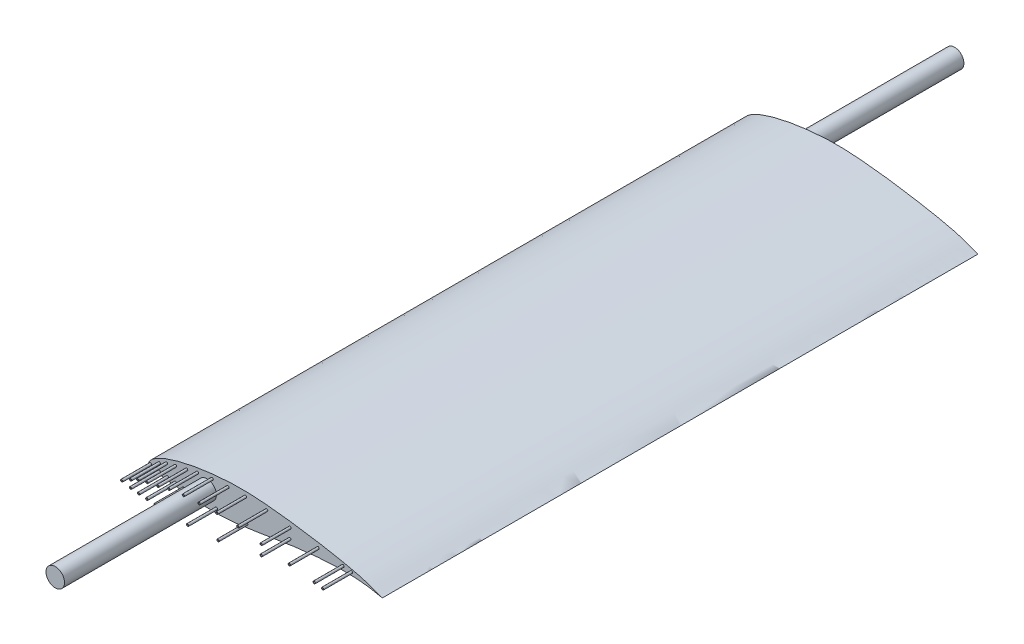
SolidWorks part; units mm, degrees
ref_plane "Front Plane" through (0, 0, 0) normal (0, 0, 1) x (1, 0, 0)
ref_plane "Top Plane" through (0, 0, 0) normal (0, 1, 0) x (1, 0, 0)
ref_plane "Right Plane" through (0, 0, 0) normal (1, 0, 0) x (0, 0, -1)
curve "Curve3"
  spline degree 3 poles (99.2573, 0.1883, 0) (100.1824, -0.0489, 0) (99.2961, 0.1993, 0) (98.6191, 0.462, 0) (97.0519, 1.0473, 0) (95.2309, 1.7549, 0) (92.9378, 2.5568, 0) (90.2536, 3.3336, 0) (87.1477, 4.0816, 0) (83.6535, 4.8449, 0) (79.8051, 5.6126, 0) (75.6551, 6.3782, 0) (71.2568, 7.1284, 0) (66.6666, 7.8484, 0) (61.9423, 8.5212, 0) (57.142, 9.1269, 0) (52.3233, 9.6447, 0) (47.5422, 10.0467, 0) (42.8474, 10.3157, 0) (38.2509, 10.3642, 0) (33.7665, 10.1859, 0) (29.4045, 9.86, 0) (25.2057, 9.3963, 0) (21.2146, 8.8145, 0) (17.4732, 8.1296, 0) (14.0211, 7.3557, 0) (10.8932, 6.51, 0) (8.1211, 5.6039, 0) (5.7296, 4.6586, 0) (3.7392, 3.6865, 0) (2.1629, 2.7162, 0) (1.0057, 1.7671, 0) (0.3099, 0.9241, 0) (0.0336, 0.3269, 0) (0.0006, 0.059, 0) (-0.0005, -0.0441, 0) (0.0087, -0.1472, 0) (0.0976, -0.2807, 0) (0.2176, -0.4056, 0) (0.6069, -0.7185, 0) (1.5156, -1.1239, 0) (3.0705, -1.583, 0) (5.1523, -2.0072, 0) (7.7279, -2.3917, 0) (10.7759, -2.7499, 0) (14.2511, -3.0772, 0) (18.0407, -3.4773, 0) (22.0414, -3.9067, 0) (26.2166, -4.1171, 0) (30.5565, -4.0983, 0) (35.1014, -3.8476, 0) (39.8555, -3.2929, 0) (44.8531, -2.5697, 0) (50.0777, -1.6972, 0) (55.4969, -0.8089, 0) (61.0345, 0.0244, 0) (66.5901, 0.7423, 0) (72.0549, 1.3013, 0) (77.3167, 1.6728, 0) (82.2608, 1.8417, 0) (86.7784, 1.812, 0) (90.7289, 1.5797, 0) (94.0476, 1.182, 0) (96.5243, 0.7715, 0) (98.476, 0.3569, 0) (99.2573, 0.1883, 0) (100.1824, -0.0489, 0) (99.2961, 0.1993, 0) knots -0.015875 -0.006971 -0.001726 0 0.001709 0.006655 0.014348 0.024259 0.036042 0.049641 0.065255 0.082793 0.102031 0.122721 0.144597 0.167375 0.190768 0.214483 0.238233 0.261741 0.284747 0.307088 0.329034 0.350455 0.371139 0.39089 0.409512 0.426831 0.442689 0.45695 0.469523 0.480322 0.48935 0.49658 0.502135 0.505254 0.506016 0.506063 0.506764 0.507486 0.508356 0.509304 0.514776 0.522722 0.53308 0.54584 0.560863 0.578018 0.596961 0.616675 0.636937 0.658148 0.680211 0.703561 0.728221 0.754164 0.781136 0.808649 0.836174 0.86317 0.889092 0.913409 0.935618 0.955187 0.97148 0.984125 0.993029 0.998274 1 1.001709 1.006655 1.014348 periodic
sketch "Sketch4" plane through (0, 0, 0) normal (0, 0, 1) x (1, 0, 0)
  spline S0 degree 3 poles (99.2573, 0.1883) (100.1824, -0.0489) (99.2961, 0.1993) (98.6191, 0.462) (97.0519, 1.0473) (95.2309, 1.7549) (92.9378, 2.5568) (90.2536, 3.3336) (87.1477, 4.0816) (83.6535, 4.8449) (79.8051, 5.6126) (75.6551, 6.3782) (71.2568, 7.1284) (66.6666, 7.8484) (61.9423, 8.5212) (57.142, 9.1269) (52.3233, 9.6447) (47.5422, 10.0467) (42.8474, 10.3157) (38.2509, 10.3642) (33.7665, 10.1859) (29.4045, 9.86) (25.2057, 9.3963) (21.2146, 8.8145) (17.4732, 8.1296) (14.0211, 7.3557) (10.8932, 6.51) (8.1211, 5.6039) (5.7296, 4.6586) (3.7392, 3.6865) (2.1629, 2.7162) (1.0057, 1.7671) (0.3099, 0.9241) (0.0336, 0.3269) (0.0006, 0.059) (-0.0005, -0.0441) (0.0087, -0.1472) (0.0976, -0.2807) (0.2176, -0.4056) (0.6069, -0.7185) (1.5156, -1.1239) (3.0705, -1.583) (5.1523, -2.0072) (7.7279, -2.3917) (10.7759, -2.7499) (14.2511, -3.0772) (18.0407, -3.4773) (22.0414, -3.9067) (26.2166, -4.1171) (30.5565, -4.0983) (35.1014, -3.8476) (39.8555, -3.2929) (44.8531, -2.5697) (50.0777, -1.6972) (55.4969, -0.8089) (61.0345, 0.0244) (66.5901, 0.7423) (72.0549, 1.3013) (77.3167, 1.6728) (82.2608, 1.8417) (86.7784, 1.812) (90.7289, 1.5797) (94.0476, 1.182) (96.5243, 0.7715) (98.476, 0.3569) (99.2573, 0.1883) (100.1824, -0.0489) (99.2961, 0.1993) knots -0.015875 -0.006971 -0.001726 0 0.001709 0.006655 0.014348 0.024259 0.036042 0.049641 0.065255 0.082793 0.102031 0.122721 0.144597 0.167375 0.190768 0.214483 0.238233 0.261741 0.284747 0.307088 0.329034 0.350455 0.371139 0.39089 0.409512 0.426831 0.442689 0.45695 0.469523 0.480322 0.48935 0.49658 0.502135 0.505254 0.506016 0.506063 0.506764 0.507486 0.508356 0.509304 0.514776 0.522722 0.53308 0.54584 0.560863 0.578018 0.596961 0.616675 0.636937 0.658148 0.680211 0.703561 0.728221 0.754164 0.781136 0.808649 0.836174 0.86317 0.889092 0.913409 0.935618 0.955187 0.97148 0.984125 0.993029 0.998274 1 1.001709 1.006655 1.014348 only from (100, 0) to (100, 0) construction
  spline S1 degree 3 poles (99.2573, 0.1883) (100.1824, -0.0489) (99.2961, 0.1993) (98.6191, 0.462) (97.0519, 1.0473) (95.2309, 1.7549) (92.9378, 2.5568) (90.2536, 3.3336) (87.1477, 4.0816) (83.6535, 4.8449) (79.8051, 5.6126) (75.6551, 6.3782) (71.2568, 7.1284) (66.6666, 7.8484) (61.9423, 8.5212) (57.142, 9.1269) (52.3233, 9.6447) (47.5422, 10.0467) (42.8474, 10.3157) (38.2509, 10.3642) (33.7665, 10.1859) (29.4045, 9.86) (25.2057, 9.3963) (21.2146, 8.8145) (17.4732, 8.1296) (14.0211, 7.3557) (10.8932, 6.51) (8.1211, 5.6039) (5.7296, 4.6586) (3.7392, 3.6865) (2.1629, 2.7162) (1.0057, 1.7671) (0.3099, 0.9241) (0.0336, 0.3269) (0.0006, 0.059) (-0.0005, -0.0441) (0.0087, -0.1472) (0.0976, -0.2807) (0.2176, -0.4056) (0.6069, -0.7185) (1.5156, -1.1239) (3.0705, -1.583) (5.1523, -2.0072) (7.7279, -2.3917) (10.7759, -2.7499) (14.2511, -3.0772) (18.0407, -3.4773) (22.0414, -3.9067) (26.2166, -4.1171) (30.5565, -4.0983) (35.1014, -3.8476) (39.8555, -3.2929) (44.8531, -2.5697) (50.0777, -1.6972) (55.4969, -0.8089) (61.0345, 0.0244) (66.5901, 0.7423) (72.0549, 1.3013) (77.3167, 1.6728) (82.2608, 1.8417) (86.7784, 1.812) (90.7289, 1.5797) (94.0476, 1.182) (96.5243, 0.7715) (98.476, 0.3569) (99.2573, 0.1883) (100.1824, -0.0489) (99.2961, 0.1993) knots -0.015875 -0.006971 -0.001726 0 0.001709 0.006655 0.014348 0.024259 0.036042 0.049641 0.065255 0.082793 0.102031 0.122721 0.144597 0.167375 0.190768 0.214483 0.238233 0.261741 0.284747 0.307088 0.329034 0.350455 0.371139 0.39089 0.409512 0.426831 0.442689 0.45695 0.469523 0.480322 0.48935 0.49658 0.502135 0.505254 0.506016 0.506063 0.506764 0.507486 0.508356 0.509304 0.514776 0.522722 0.53308 0.54584 0.560863 0.578018 0.596961 0.616675 0.636937 0.658148 0.680211 0.703561 0.728221 0.754164 0.781136 0.808649 0.836174 0.86317 0.889092 0.913409 0.935618 0.955187 0.97148 0.984125 0.993029 0.998274 1 1.001709 1.006655 1.014348 only from (100, 0) to (100, 0)
extrude "Boss-Extrude12" add sketch "Sketch4" along normal mid plane 255
sketch "Sketch5" plane through (0, 0, 127.5) normal (0, 0, 1) x (1, 0, 0)
  line L0 (100, 0) -> (100, 7.5325) construction
  circle A1 centre (25, 2.7) radius 3.9688
  spline S0 degree 3 poles (99.2573, 0.1883) (100.1824, -0.0489) (99.2961, 0.1993) (98.6191, 0.462) (97.0519, 1.0473) (95.2309, 1.7549) (92.9378, 2.5568) (90.2536, 3.3336) (87.1477, 4.0816) (83.6535, 4.8449) (79.8051, 5.6126) (75.6551, 6.3782) (71.2568, 7.1284) (66.6666, 7.8484) (61.9423, 8.5212) (57.142, 9.1269) (52.3233, 9.6447) (47.5422, 10.0467) (42.8474, 10.3157) (38.2509, 10.3642) (33.7665, 10.1859) (29.4045, 9.86) (25.2057, 9.3963) (21.2146, 8.8145) (17.4732, 8.1296) (14.0211, 7.3557) (10.8932, 6.51) (8.1211, 5.6039) (5.7296, 4.6586) (3.7392, 3.6865) (2.1629, 2.7162) (1.0057, 1.7671) (0.3099, 0.9241) (0.0336, 0.3269) (0.0006, 0.059) (-0.0005, -0.0441) (0.0087, -0.1472) (0.0976, -0.2807) (0.2176, -0.4056) (0.6069, -0.7185) (1.5156, -1.1239) (3.0705, -1.583) (5.1523, -2.0072) (7.7279, -2.3917) (10.7759, -2.7499) (14.2511, -3.0772) (18.0407, -3.4773) (22.0414, -3.9067) (26.2166, -4.1171) (30.5565, -4.0983) (35.1014, -3.8476) (39.8555, -3.2929) (44.8531, -2.5697) (50.0777, -1.6972) (55.4969, -0.8089) (61.0345, 0.0244) (66.5901, 0.7423) (72.0549, 1.3013) (77.3167, 1.6728) (82.2608, 1.8417) (86.7784, 1.812) (90.7289, 1.5797) (94.0476, 1.182) (96.5243, 0.7715) (98.476, 0.3569) (99.2573, 0.1883) (100.1824, -0.0489) (99.2961, 0.1993) knots -0.015875 -0.006971 -0.001726 0 0.001709 0.006655 0.014348 0.024259 0.036042 0.049641 0.065255 0.082793 0.102031 0.122721 0.144597 0.167375 0.190768 0.214483 0.238233 0.261741 0.284747 0.307088 0.329034 0.350455 0.371139 0.39089 0.409512 0.426831 0.442689 0.45695 0.469523 0.480322 0.48935 0.49658 0.502135 0.505254 0.506016 0.506063 0.506764 0.507486 0.508356 0.509304 0.514776 0.522722 0.53308 0.54584 0.560863 0.578018 0.596961 0.616675 0.636937 0.658148 0.680211 0.703561 0.728221 0.754164 0.781136 0.808649 0.836174 0.86317 0.889092 0.913409 0.935618 0.955187 0.97148 0.984125 0.993029 0.998274 1 1.001709 1.006655 1.014348 only from (100, 0) to (100, 0) construction
  dimension "D4" = 7.9375
  dimension "D1" = 100
  dimension "D2" = 25
  dimension "D3" = 2.7
extrude "Boss-Extrude13" add sketch "Sketch5" along normal blind 65
mirror "Mirror1" about plane through (0, 0, 0) normal (0, 0, 1) of "Boss-Extrude13"
sketch "Sketch6" plane through (0, 0, 127.5) normal (0, 0, 1) x (1, 0, 0)
  line L0 (51.5475, 9.6988) -> (56.9104, 9.1388) construction
  line L1 (41.449, 10.3172) -> (44.1311, 10.2279) construction
  circle A0 centre (0.75, 0) radius 0.495
  circle A1 centre (0.75, 0) radius 0.325
  circle A2 centre (86.76, 3) radius 0.495
  circle A3 centre (86.76, 3) radius 0.325
  circle A4 centre (83.16, 3.5) radius 0.495
  circle A5 centre (83.16, 3.5) radius 0.325
  circle A6 centre (72.5, 4.8) radius 0.495
  circle A7 centre (72.5, 4.8) radius 0.325
  circle A8 centre (60.4429, 6.3) radius 0.495
  circle A9 centre (60.4429, 6.3) radius 0.325
  circle A10 centre (60.4429, 2.15) radius 0.495
  circle A11 centre (60.4429, 2.15) radius 0.325
  circle A12 centre (50.4652, 7.8009) radius 0.495
  circle A13 centre (50.4652, 7.8009) radius 0.325
  circle A14 centre (41.4199, 8.317) radius 0.495
  circle A15 centre (41.4199, 8.317) radius 0.325
  circle A16 centre (41.4199, 8.317) radius 0.495
  circle A17 centre (41.4199, 8.317) radius 0.325
  circle A18 centre (33.8799, 8.117) radius 0.495
  circle A19 centre (33.8799, 8.117) radius 0.325
  circle A20 centre (27.1399, 7.767) radius 0.495
  circle A21 centre (27.1399, 7.767) radius 0.325
  circle A22 centre (20.9099, 6.967) radius 0.495
  circle A23 centre (20.9099, 6.967) radius 0.325
  circle A26 centre (16.221, 5.767) radius 0.495
  circle A27 centre (16.221, 5.767) radius 0.325
  circle A28 centre (11.4855, 4.767) radius 0.495
  circle A29 centre (11.4855, 4.767) radius 0.325
  circle A30 centre (7.6125, 3.767) radius 0.495
  circle A31 centre (7.6125, 3.767) radius 0.325
  circle A36 centre (4.5056, 2.267) radius 0.495
  circle A37 centre (4.5056, 2.267) radius 0.325
  circle A38 centre (4.5056, -0.85) radius 0.495
  circle A39 centre (4.5056, -0.85) radius 0.325
  circle A40 centre (7.9928, -1.15) radius 0.495
  circle A41 centre (7.9928, -1.15) radius 0.325
  circle A42 centre (11.4799, -1.45) radius 0.495
  circle A43 centre (11.4799, -1.45) radius 0.325
  circle A44 centre (14.9569, -1.85) radius 0.495
  circle A45 centre (14.9569, -1.85) radius 0.325
  circle A46 centre (28.948, -2.35) radius 0.495
  circle A47 centre (28.948, -2.35) radius 0.325
  circle A48 centre (41.9234, -1.55) radius 0.495
  circle A49 centre (41.9234, -1.55) radius 0.325
  spline S2 degree 3 poles (99.2573, 0.1883) (100.1824, -0.0489) (99.2961, 0.1993) (98.6191, 0.462) (97.0519, 1.0473) (95.2309, 1.7549) (92.9378, 2.5568) (90.2536, 3.3336) (87.1477, 4.0816) (83.6535, 4.8449) (79.8051, 5.6126) (75.6551, 6.3782) (71.2568, 7.1284) (66.6666, 7.8484) (61.9423, 8.5212) (57.142, 9.1269) (52.3233, 9.6447) (47.5422, 10.0467) (42.8474, 10.3157) (38.2509, 10.3642) (33.7665, 10.1859) (29.4045, 9.86) (25.2057, 9.3963) (21.2146, 8.8145) (17.4732, 8.1296) (14.0211, 7.3557) (10.8932, 6.51) (8.1211, 5.6039) (5.7296, 4.6586) (3.7392, 3.6865) (2.1629, 2.7162) (1.0057, 1.7671) (0.3099, 0.9241) (0.0336, 0.3269) (0.0006, 0.059) (-0.0005, -0.0441) (0.0087, -0.1472) (0.0976, -0.2807) (0.2176, -0.4056) (0.6069, -0.7185) (1.5156, -1.1239) (3.0705, -1.583) (5.1523, -2.0072) (7.7279, -2.3917) (10.7759, -2.7499) (14.2511, -3.0772) (18.0407, -3.4773) (22.0414, -3.9067) (26.2166, -4.1171) (30.5565, -4.0983) (35.1014, -3.8476) (39.8555, -3.2929) (44.8531, -2.5697) (50.0777, -1.6972) (55.4969, -0.8089) (61.0345, 0.0244) (66.5901, 0.7423) (72.0549, 1.3013) (77.3167, 1.6728) (82.2608, 1.8417) (86.7784, 1.812) (90.7289, 1.5797) (94.0476, 1.182) (96.5243, 0.7715) (98.476, 0.3569) (99.2573, 0.1883) (100.1824, -0.0489) (99.2961, 0.1993) knots -0.015875 -0.006971 -0.001726 0 0.001709 0.006655 0.014348 0.024259 0.036042 0.049641 0.065255 0.082793 0.102031 0.122721 0.144597 0.167375 0.190768 0.214483 0.238233 0.261741 0.284747 0.307088 0.329034 0.350455 0.371139 0.39089 0.409512 0.426831 0.442689 0.45695 0.469523 0.480322 0.48935 0.49658 0.502135 0.505254 0.506016 0.506063 0.506764 0.507486 0.508356 0.509304 0.514776 0.522722 0.53308 0.54584 0.560863 0.578018 0.596961 0.616675 0.636937 0.658148 0.680211 0.703561 0.728221 0.754164 0.781136 0.808649 0.836174 0.86317 0.889092 0.913409 0.935618 0.955187 0.97148 0.984125 0.993029 0.998274 1 1.001709 1.006655 1.014348 only from (100, 0) to (100, 0) construction
  spline S3 degree 3 poles (99.2573, 0.1883) (100.1824, -0.0489) (99.2961, 0.1993) (98.6191, 0.462) (97.0519, 1.0473) (95.2309, 1.7549) (92.9378, 2.5568) (90.2536, 3.3336) (87.1477, 4.0816) (83.6535, 4.8449) (79.8051, 5.6126) (75.6551, 6.3782) (71.2568, 7.1284) (66.6666, 7.8484) (61.9423, 8.5212) (57.142, 9.1269) (52.3233, 9.6447) (47.5422, 10.0467) (42.8474, 10.3157) (38.2509, 10.3642) (33.7665, 10.1859) (29.4045, 9.86) (25.2057, 9.3963) (21.2146, 8.8145) (17.4732, 8.1296) (14.0211, 7.3557) (10.8932, 6.51) (8.1211, 5.6039) (5.7296, 4.6586) (3.7392, 3.6865) (2.1629, 2.7162) (1.0057, 1.7671) (0.3099, 0.9241) (0.0336, 0.3269) (0.0006, 0.059) (-0.0005, -0.0441) (0.0087, -0.1472) (0.0976, -0.2807) (0.2176, -0.4056) (0.6069, -0.7185) (1.5156, -1.1239) (3.0705, -1.583) (5.1523, -2.0072) (7.7279, -2.3917) (10.7759, -2.7499) (14.2511, -3.0772) (18.0407, -3.4773) (22.0414, -3.9067) (26.2166, -4.1171) (30.5565, -4.0983) (35.1014, -3.8476) (39.8555, -3.2929) (44.8531, -2.5697) (50.0777, -1.6972) (55.4969, -0.8089) (61.0345, 0.0244) (66.5901, 0.7423) (72.0549, 1.3013) (77.3167, 1.6728) (82.2608, 1.8417) (86.7784, 1.812) (90.7289, 1.5797) (94.0476, 1.182) (96.5243, 0.7715) (98.476, 0.3569) (99.2573, 0.1883) (100.1824, -0.0489) (99.2961, 0.1993) knots -0.015875 -0.006971 -0.001726 0 0.001709 0.006655 0.014348 0.024259 0.036042 0.049641 0.065255 0.082793 0.102031 0.122721 0.144597 0.167375 0.190768 0.214483 0.238233 0.261741 0.284747 0.307088 0.329034 0.350455 0.371139 0.39089 0.409512 0.426831 0.442689 0.45695 0.469523 0.480322 0.48935 0.49658 0.502135 0.505254 0.506016 0.506063 0.506764 0.507486 0.508356 0.509304 0.514776 0.522722 0.53308 0.54584 0.560863 0.578018 0.596961 0.616675 0.636937 0.658148 0.680211 0.703561 0.728221 0.754164 0.781136 0.808649 0.836174 0.86317 0.889092 0.913409 0.935618 0.955187 0.97148 0.984125 0.993029 0.998274 1 1.001709 1.006655 1.014348 only from (100, 0) to (100, 0)
  dimension "D1" = 0.99
  dimension "D2" = 0.75
  dimension "D3" = 0.65
  dimension "D4" = 0.99
  dimension "D5" = 0.65
  dimension "D7" = 3
  dimension "D8" = 0.99
  dimension "D11" = 0.65
  dimension "D14" = 0.99
  dimension "D15" = 0.65
  dimension "D16" = 0.99
  dimension "D19" = 0.65
  dimension "D20" = 0.99
  dimension "D21" = 0.65
  dimension "D24" = 0.99
  dimension "D25" = 0.65
  dimension "D28" = 0.99
  dimension "D32" = 0.65
  dimension "D35" = 0.99
  dimension "D36" = 0.65
  dimension "D39" = 0.99
  dimension "D40" = 0.65
  dimension "D42" = 0.99
  dimension "D43" = 0.65
  dimension "D46" = 0.99
  dimension "D47" = 0.65
  dimension "D50" = 0.99
  dimension "D51" = 0.65
  dimension "D54" = 0.99
  dimension "D55" = 0.65
  dimension "D58" = 0.99
  dimension "D59" = 0.65
  dimension "D60" = 0.99
  dimension "D61" = 0.65
  dimension "D62" = 0.99
  dimension "D63" = 0.65
  dimension "D64" = 0.99
  dimension "D65" = 0.65
  dimension "D66" = 0.99
  dimension "D67" = 0.65
  dimension "D68" = 0.65
  dimension "D69" = 0.99
  dimension "D70" = 0.99
  dimension "D71" = 0.65
  dimension "D6" = 13.24
  dimension "D9" = 3.6
  dimension "D10" = 0.5
  dimension "D12" = 10.66
  dimension "D13" = 1.3
  dimension "D17" = 12.15
  dimension "D18" = 1.5
  dimension "D22" = 4.15
  dimension "D23" = 4.84
  dimension "D26" = 10.09
  dimension "D27" = 1.5009
  dimension "D29" = 9.06
  dimension "D30" = 2
  dimension "D31" = 0.5161
  dimension "D33" = 7.54
  dimension "D34" = 0.2
  dimension "D37" = 6.74
  dimension "D38" = 0.35
  dimension "D41" = 6.23
  dimension "D44" = 0.8
  dimension "D45" = 1.2
  dimension "D48" = 4.84
  dimension "D49" = 1
  dimension "D52" = 4
  dimension "D53" = 1
  dimension "D56" = 3.45
  dimension "D57" = 1.5
  dimension "D72" = 0.85
  dimension "D73" = 3.5
  dimension "D74" = 0.3
  dimension "D75" = 3.5
  dimension "D76" = 0.3
  dimension "D77" = 3.5
  dimension "D78" = 0.4
  dimension "D79" = 14
  dimension "D80" = 0.5
  dimension "D81" = 13
  dimension "D82" = 0.8
extrude "Boss-Extrude14" add sketch "Sketch6" along normal blind 12.3 contours A14 A15 | A12 A13 | A8 A9 | A10 A11 | A6 A7 | A4 A5 | A2 A3 | A18 | A20 | A22 | A23 | A21 | A19 | A26 | A28 | A29 | A27 | A31 | A30 | A40 | A41 | A42 | A43 | A44 | A45 | A46 | A47 | A48 | A49 | A0 | A1 | A36 | A37 | A38 | A39
